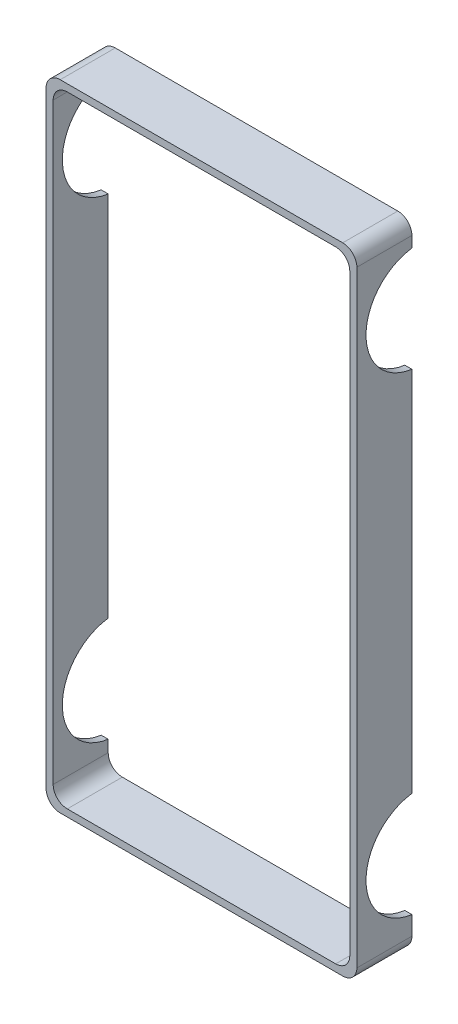
SolidWorks part; units mm, degrees
material "ABS"
ref_plane "前视基准面" through (0, 0, 0) normal (0, 0, 1) x (1, 0, 0)
ref_plane "上视基准面" through (0, 0, 0) normal (0, 1, 0) x (1, 0, 0)
ref_plane "右视基准面" through (0, 0, 0) normal (1, 0, 0) x (0, 0, -1)
sketch "草图1" plane through (0, 0, 0) normal (0, 0, 1) x (1, 0, 0)
  line L1 (-260, -450) -> (180.4, -450)
  line L2 (-260, -450) -> (-260, 450)
  line L3 (-260, 450) -> (180.4, 450)
  line L4 (180.4, -450) -> (180.4, 450)
  line L5 (-250, -440) -> (170.4, -440)
  line L6 (-250, -440) -> (-250, 440)
  line L7 (-250, 440) -> (170.4, 440)
  line L8 (170.4, -440) -> (170.4, 440)
  point P0 (0, 0)
  point P6 (0, 0)
  dimension "D1" = 440.4
  dimension "D2" = 900
  dimension "D3" = 420.4
  dimension "D4" = 880
extrude "凸台-拉伸1" add sketch "草图1" along normal blind 78
fillet "圆角1" radius 20 4 edges at (-260, -450, 39) (-260, 450, 39) (180.4, -450, 39) (180.4, 450, 39)
fillet "圆角2" radius 20 4 edges at (-250, 440, 39) (170.4, 440, 39) (-250, -440, 39) (170.4, -440, 39)
sketch "草图2" plane through (180.4, 0, 0) normal (1, 0, 0) x (0, 0, -1)
  line L0 (0, 265.8197) -> (0, 414.4803)
  line L1 (0, -430) -> (0, 430) construction
  arc A1 (0, 414.4803) -> (0, 265.8197) centre (10, 340.15) ccw
extrude "切除-拉伸1" cut sketch "草图2" against normal blind 730
sketch "草图3" plane through (180.4, 0, 0) normal (1, 0, 0) x (0, 0, -1)
  line L0 (0, -403.4703) -> (0, -254.8097)
  arc A1 (0, -254.8097) -> (0, -403.4703) centre (10, -329.14) ccw
extrude "切除-拉伸2" cut sketch "草图3" against normal blind 730
